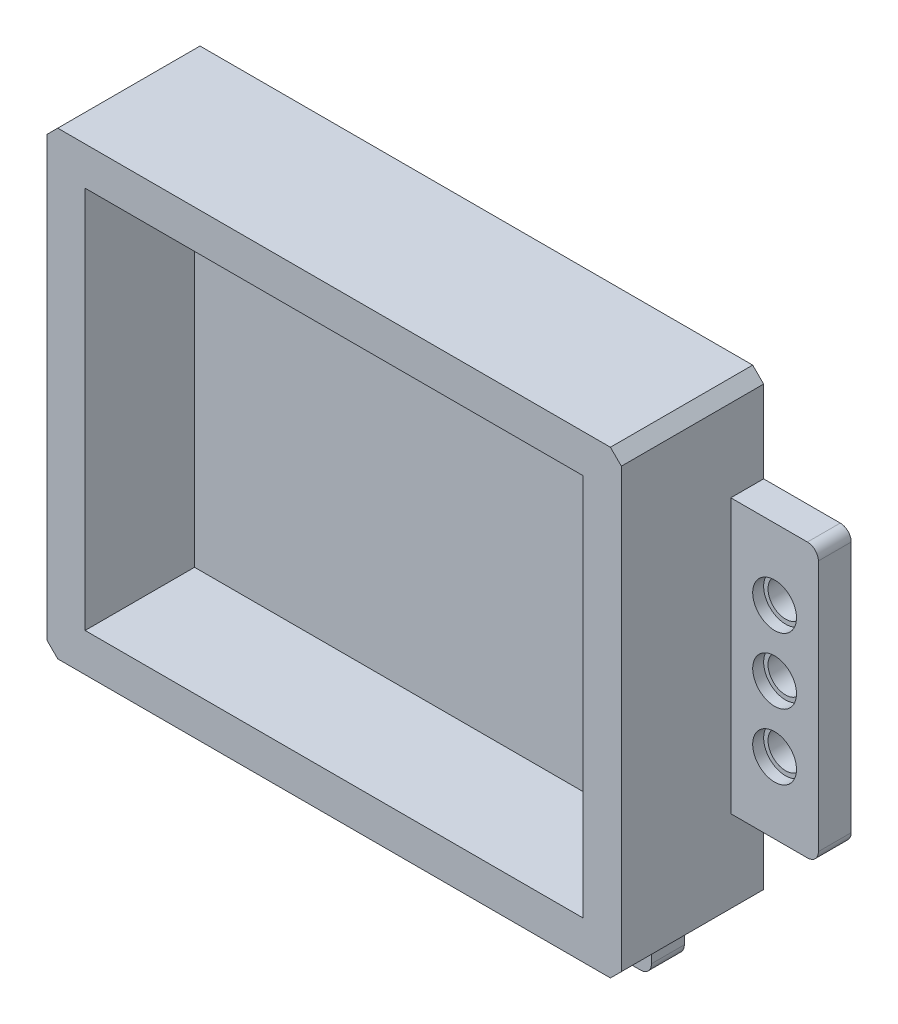
SolidWorks part; units mm, degrees
ref_plane "Alzado" through (0, 0, 0) normal (0, 0, 1) x (1, 0, 0)
ref_plane "Planta" through (0, 0, 0) normal (0, 1, 0) x (1, 0, 0)
ref_plane "Vista lateral" through (0, 0, 0) normal (1, 0, 0) x (0, 0, -1)
sketch "Croquis1" plane through (0, 0, 0) normal (0, 0, 1) x (1, 0, 0)
  line L1 (-22.75, -17.5) -> (22.75, -17.5)
  line L2 (-22.75, -17.5) -> (-22.75, 17.5)
  line L3 (-22.75, 17.5) -> (22.75, 17.5)
  line L4 (22.75, -17.5) -> (22.75, 17.5)
  line L5 (-22.75, -17.5) -> (22.75, 17.5) construction
  line L6 (-22.75, 17.5) -> (22.75, -17.5) construction
  line L7 (-26.25, -21) -> (26.25, -21)
  line L8 (-26.25, -21) -> (-26.25, 21)
  line L9 (-26.25, 21) -> (26.25, 21)
  line L10 (26.25, -21) -> (26.25, 21)
  line L11 (-26.25, -21) -> (26.25, 21) construction
  line L12 (-26.25, 21) -> (26.25, -21) construction
  point P0 (0, 0)
  point P6 (0, 0)
  dimension "D1" = 35
  dimension "D2" = 3.5
  dimension "45" = 45.5
  dimension "D3" = 3.5
extrude "Saliente-Extruir1" add sketch "Croquis1" along normal blind 10
sketch "Croquis3" plane through (0, 0, 0) normal (0, 0, 1) x (1, 0, 0)
  line L1 (-26.25, -21) -> (26.25, -21)
  line L2 (-26.25, -21) -> (-26.25, 21)
  line L3 (-26.25, 21) -> (26.25, 21)
  line L4 (26.25, -21) -> (26.25, 21)
  line L5 (-26.25, -21) -> (26.25, 21) construction
  line L6 (-26.25, 21) -> (26.25, -21) construction
  point P0 (0, 0)
extrude "Saliente-Extruir2" add sketch "Croquis3" against normal blind 3
sketch "Croquis4" plane through (0, -21, 0) normal (0, -1, 0) x (1, 0, 0)
  line L0 (-19, -3) -> (19, -3)
  line L1 (-26.25, -3) -> (26.25, -3) construction
  line L2 (-19, -3) -> (-19, 0)
  line L3 (-19, 0) -> (19, 0)
  line L4 (19, 0) -> (19, -3)
  point P6 (0, -3)
  dimension "D1" = 38
  dimension "D2" = 3
extrude "Saliente-Extruir3" add sketch "Croquis4" along normal blind 8
sketch "Croquis5" plane through (0, 0, 0) normal (0, 0, 1) x (1, 0, 0)
  line L0 (-19, -29) -> (-19, -21) construction
  circle A0 centre (-12, -25) radius 2
  circle A1 centre (-6, -25) radius 2
  circle A2 centre (0, -25) radius 2
  circle A3 centre (6, -25) radius 2
  circle A4 centre (12, -25) radius 2
  point P12 (-19, -25)
  dimension "D1" = 6
  dimension "D5" = 4
  dimension "D6" = 4
  dimension "D7" = 4
  dimension "D8" = 4
  dimension "D9" = 4
  dimension "D2" = 6
  dimension "D3" = 6
  dimension "D4" = 6
extrude "Cortar-Extruir1" cut sketch "Croquis5" against normal blind 1
sketch "Croquis6" plane through (0, 0, -1) normal (0, 0, 1) x (1, 0, 0)
  circle A0 centre (-12, -25) radius 1.6
  circle A1 centre (-6, -25) radius 1.6
  circle A2 centre (0, -25) radius 1.6
  circle A3 centre (6, -25) radius 1.6
  circle A4 centre (12, -25) radius 1.6
  dimension "D1" = 3.2
  dimension "D2" = 3.2
  dimension "D3" = 3.2
  dimension "D4" = 3.2
  dimension "D5" = 3.2
extrude "Cortar-Extruir2" cut sketch "Croquis6" against normal blind 4
sketch "Croquis7" plane through (26.25, 0, 0) normal (1, 0, 0) x (0, 0, -1)
  line L0 (3, -12.5) -> (3, 12.5)
  line L1 (3, -21) -> (3, 21) construction
  line L2 (3, -12.5) -> (0, -12.5)
  line L3 (0, -12.5) -> (0, 12.5)
  line L4 (0, 12.5) -> (3, 12.5)
  point P0 (3, 0)
  point P5 (3, 0)
  dimension "D1" = 25
extrude "Saliente-Extruir4" add sketch "Croquis7" along normal blind 8
sketch "Croquis8" plane through (0, 0, 0) normal (0, 0, 1) x (1, 0, 0)
  line L0 (34.25, -12.5) -> (26.25, -12.5) construction
  circle A0 centre (30.25, 6) radius 2
  circle A1 centre (30.25, 0) radius 2
  circle A2 centre (30.25, -6) radius 2
  point P6 (0, 0)
  point P10 (30.25, -12.5)
  dimension "D3" = 4
  dimension "D4" = 4
  dimension "D5" = 4
  dimension "D1" = 6
  dimension "D2" = 6
extrude "Cortar-Extruir3" cut sketch "Croquis8" against normal blind 1
sketch "Croquis9" plane through (0, 0, -3) normal (0, 0, -1) x (-1, 0, 0)
  circle A0 centre (-30.25, 6) radius 1.6
  circle A1 centre (-30.25, 0) radius 1.6
  circle A2 centre (-30.25, -6) radius 1.6
  dimension "D1" = 3.2
  dimension "D2" = 3.2
  dimension "D3" = 3.2
extrude "Cortar-Extruir4" cut sketch "Croquis9" against normal blind 3
chamfer "Chaflán1" distance 1 angle 45 4 edges at (26.25, 21, 3.5) (26.25, -21, 3.5) (-26.25, -21, 3.5) (-26.25, 21, 3.5)
fillet "Redondeo2" radius 1 4 edges at (-19, -29, -1.5) (19, -29, -1.5) (34.25, 12.5, -1.5) (34.25, -12.5, -1.5)
